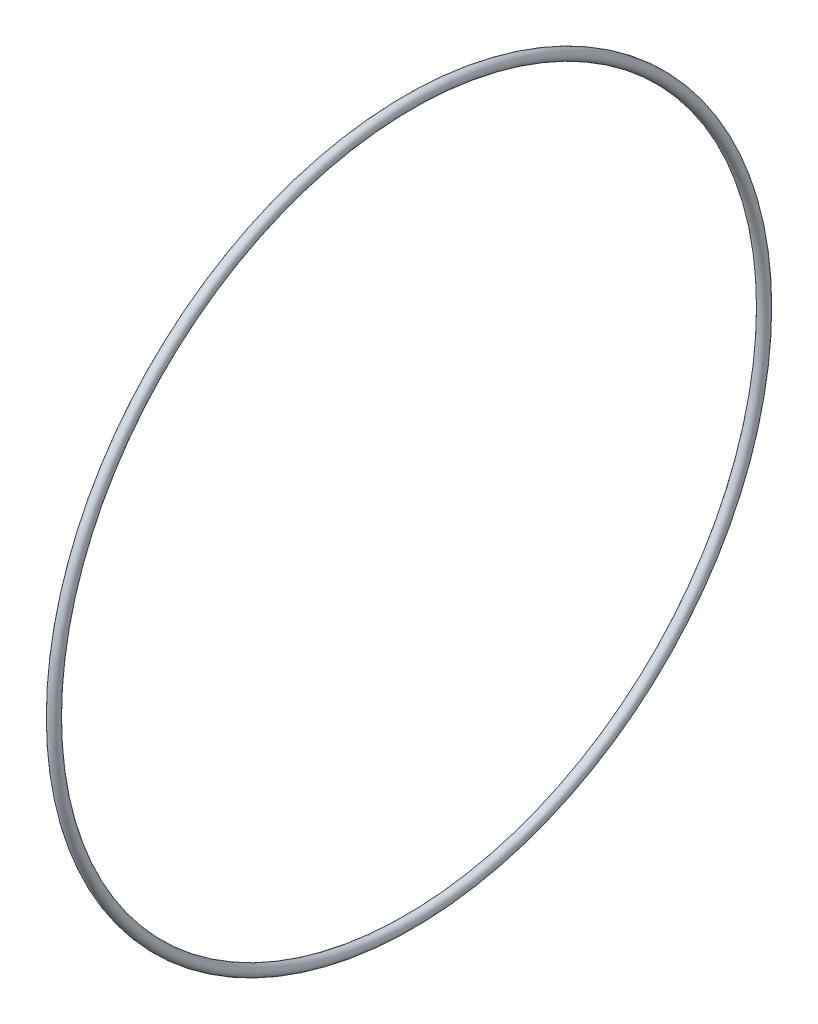
SolidWorks part; units mm, degrees
ref_plane "Front Plane" through (0, 0, 0) normal (0, 0, 1) x (1, 0, 0)
ref_plane "Top Plane" through (0, 0, 0) normal (0, 1, 0) x (1, 0, 0)
ref_plane "Right Plane" through (0, 0, 0) normal (1, 0, 0) x (0, 0, -1)
sketch "Sketch1" plane through (0, 0, 0) normal (0, 0, 1) x (1, 0, 0)
  circle A0 centre (0, 110) radius 1.6667
  dimension "D1" = 3.3333
  dimension "D2" = 110
ref_axis "Axis1" through (-73.3428, 0, 0) along (1, 0, 0)
revolve "Revolve1" add sketch "Sketch1" angle 360 about axis through (-73.3428, 0, 0) along (1, 0, 0)
